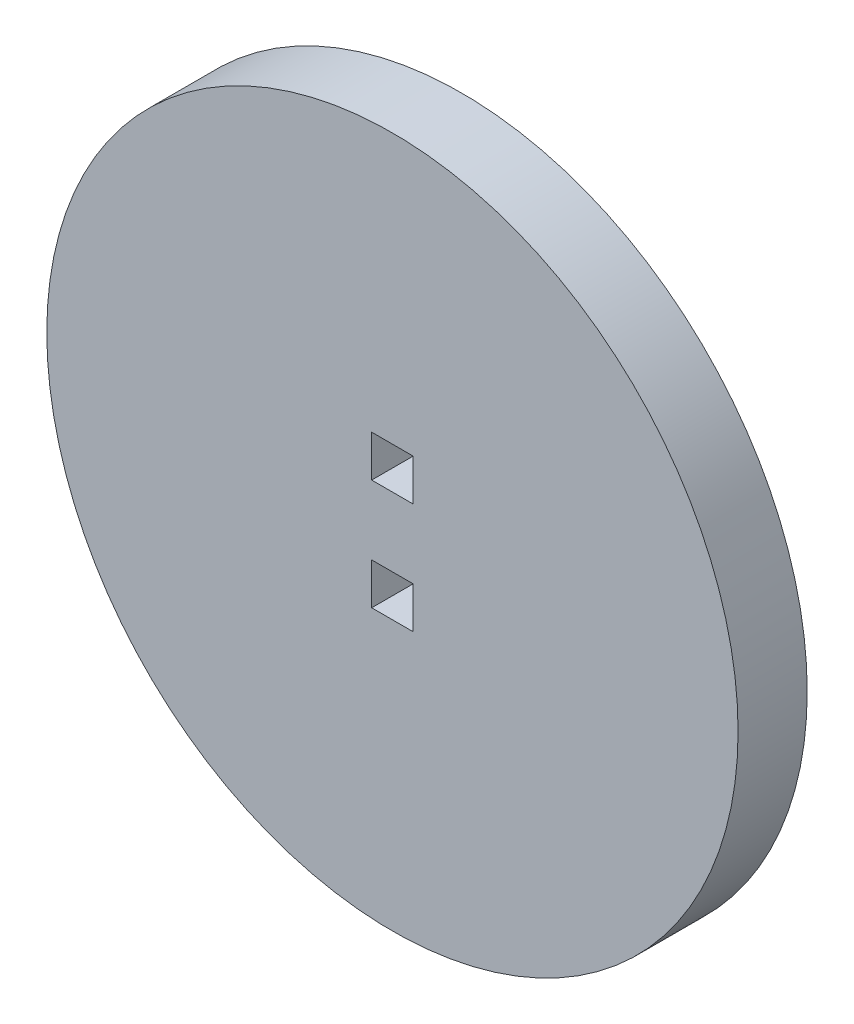
SolidWorks part; units mm, degrees
ref_plane "Front Plane" through (0, 0, 0) normal (0, 0, 1) x (1, 0, 0)
ref_plane "Top Plane" through (0, 0, 0) normal (0, 1, 0) x (1, 0, 0)
ref_plane "Right Plane" through (0, 0, 0) normal (1, 0, 0) x (0, 0, -1)
sketch "Sketch1" plane through (0, 0, 0) normal (0, 0, 1) x (1, 0, 0)
  circle A0 centre (0, 0) radius 25
  dimension "D1" = 50
extrude "Boss-Extrude1" add sketch "Sketch1" along normal blind 5
sketch "Sketch2" plane through (0, 0, 5) normal (0, 0, 1) x (1, 0, 0)
  line L5 (-1.5, -2.5) -> (1.5, -2.5)
  line L6 (-1.5, -2.5) -> (-1.5, -5.5)
  line L7 (-1.5, -5.5) -> (1.5, -5.5)
  line L8 (1.5, -2.5) -> (1.5, -5.5)
  line L9 (-1.5, -2.5) -> (1.5, -5.5) construction
  line L10 (-1.5, -5.5) -> (1.5, -2.5) construction
  line L11 (-1.5, 5.5) -> (1.5, 5.5)
  line L12 (-1.5, 5.5) -> (-1.5, 2.5)
  line L13 (-1.5, 2.5) -> (1.5, 2.5)
  line L14 (1.5, 5.5) -> (1.5, 2.5)
  line L15 (-1.5, 5.5) -> (1.5, 2.5) construction
  line L16 (-1.5, 2.5) -> (1.5, 5.5) construction
  point P0 (0, -4)
  point P6 (0, 4)
  point P11 (0, 0)
  point P13 (0, 0)
  point P14 (0, 0)
  dimension "D1" = 3
  dimension "D2" = 3
  dimension "D3" = 3
  dimension "D4" = 3
  dimension "D5" = 4
  dimension "D6" = 4
extrude "Cut-Extrude1" cut sketch "Sketch2" against normal through all
